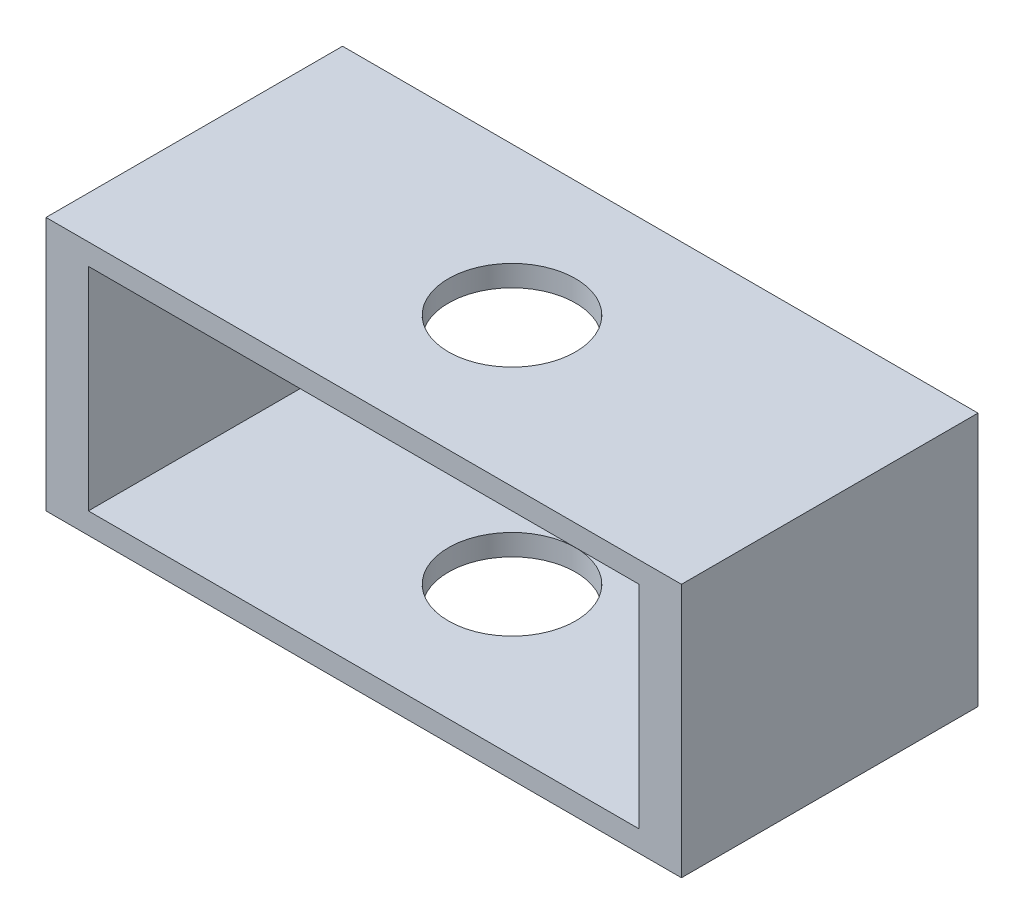
SolidWorks part; units mm, degrees
ref_plane "Спереди" through (0, 0, 0) normal (0, 0, 1) x (1, 0, 0)
ref_plane "Сверху" through (0, 0, 0) normal (0, 1, 0) x (1, 0, 0)
ref_plane "Справа" through (0, 0, 0) normal (1, 0, 0) x (0, 0, -1)
sketch "Эскиз1" plane through (0, 0, 0) normal (0, 1, 0) x (1, 0, 0)
  line L1 (-15, -7) -> (15, -7)
  line L2 (-15, -7) -> (-15, 7)
  line L3 (-15, 7) -> (15, 7)
  line L4 (15, -7) -> (15, 7)
  line L5 (-15, -7) -> (15, 7) construction
  line L6 (-15, 7) -> (15, -7) construction
  circle A0 centre (0, 0) radius 3
  point P0 (0, 0)
  dimension "D3" = 6
  dimension "D1" = 30
  dimension "D2" = 14
extrude "Бобышка-Вытянуть1" add sketch "Эскиз1" along normal blind 1
sketch "Эскиз2" plane through (0, 1, 0) normal (0, 1, 0) x (1, 0, 0)
  line L0 (-1000, 0) -> (49000, 0) construction
  line L1 (0, -1000) -> (0, 49000) construction
  line L2 (-15, 7) -> (-15, -7) construction
  line L3 (-15, 7) -> (-15, -7)
  line L4 (13, 7) -> (15, -7) construction
  line L5 (-13, -7) -> (-15, -7)
  line L6 (-13, -7) -> (-13, 7)
  line L7 (-13, 7) -> (-15, 7)
  line L8 (-15, -7) -> (-15, 7)
  line L9 (-13, -7) -> (-15, 7) construction
  line L10 (-13, 7) -> (-15, -7) construction
  line L11 (13, -7) -> (15, 7) construction
  line L12 (15, -7) -> (15, 7)
  line L13 (13, 7) -> (15, 7)
  line L14 (13, -7) -> (13, 7)
  line L15 (13, -7) -> (15, -7)
  line L16 (15, 7) -> (15, -7)
  point P7 (-14, 0)
  point P15 (14, 0)
  line M6 (15, -7) -> (15, 7)
  line M7 (15, 7) -> (-15, 7)
  line M8 (-15, 7) -> (-15, -7)
  line M9 (-15, -7) -> (15, -7)
  dimension "D1" = 2
extrude "Бобышка-Вытянуть2" add sketch "Эскиз2" along normal blind 10 contours L6 M9 M7 M8 | L14 M9 M6 M7
sketch "Эскиз3" plane through (0, 11, 0) normal (0, 1, 0) x (1, 0, 0)
  line L1 (-15, -7) -> (15, -7)
  line L2 (-15, -7) -> (-15, 7)
  line L3 (-15, 7) -> (15, 7)
  line L4 (15, -7) -> (15, 7)
  line L5 (-15, -7) -> (15, 7) construction
  line L6 (-15, 7) -> (15, -7) construction
  circle A0 centre (0, 0) radius 3
  point P0 (0, 0)
  dimension "D1" = 6
extrude "Бобышка-Вытянуть3" add sketch "Эскиз3" along normal blind 1
